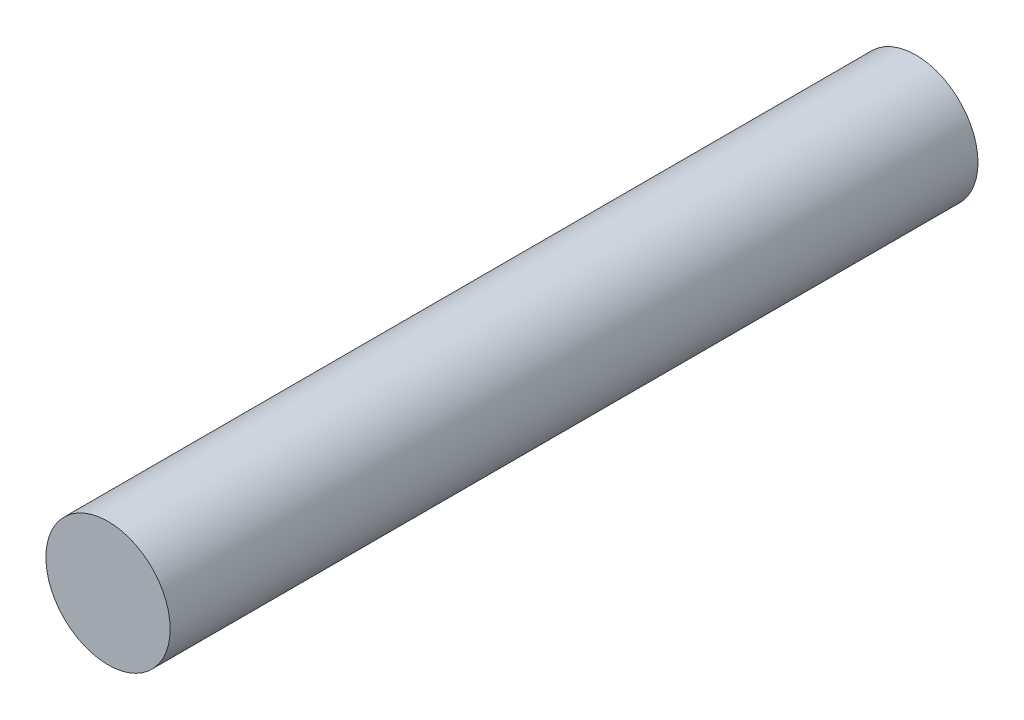
SolidWorks part; units mm, degrees
material "AISI 1020"
ref_plane "Front Plane" through (0, 0, 0) normal (0, 0, 1) x (1, 0, 0)
ref_plane "Top Plane" through (0, 0, 0) normal (0, 1, 0) x (1, 0, 0)
ref_plane "Right Plane" through (0, 0, 0) normal (1, 0, 0) x (0, 0, -1)
sketch "Sketch1" plane through (0, 0, 0) normal (0, 0, 1) x (1, 0, 0)
  circle A0 centre (0, 0) radius 3
  dimension "D1" = 6
extrude "Boss-Extrude1" add sketch "Sketch1" along normal blind 39
